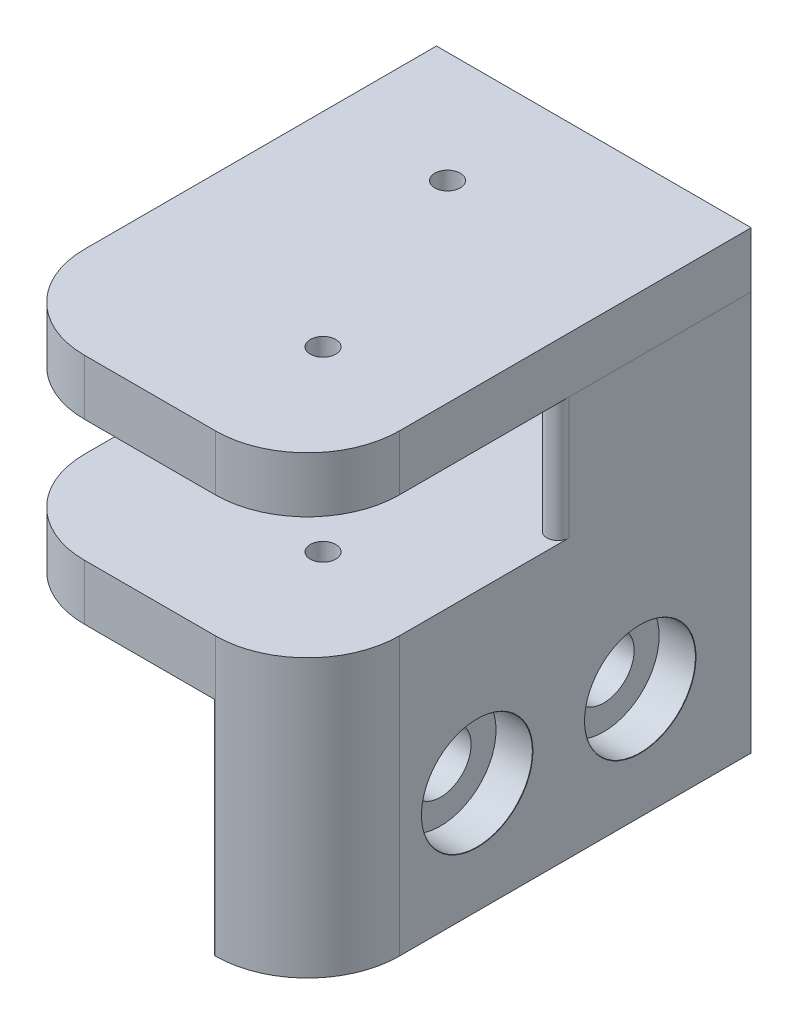
SolidWorks part; units mm, degrees
ref_plane "Front Plane" through (0, 0, 0) normal (0, 0, 1) x (1, 0, 0)
ref_plane "Top Plane" through (0, 0, 0) normal (0, 1, 0) x (1, 0, 0)
ref_plane "Right Plane" through (0, 0, 0) normal (1, 0, 0) x (0, 0, -1)
sketch "Sketch1" plane through (0, 0, 0) normal (0, 1, 0) x (1, 0, 0)
  line L1 (-14.185, -20) -> (14.185, -20)
  line L2 (-14.185, -20) -> (-14.185, 20)
  line L3 (-14.185, 20) -> (14.185, 20)
  line L4 (14.185, -20) -> (14.185, 20)
  line L5 (-14.185, -20) -> (14.185, 20) construction
  line L6 (-14.185, 20) -> (14.185, -20) construction
  point P0 (0, 0)
  dimension "D1" = 28.37
  dimension "D2" = 40
extrude "Boss-Extrude1" add sketch "Sketch1" along normal blind 5
sketch "Sketch2" plane through (0, 0, 0) normal (0, -1, 0) x (1, 0, 0)
  line L0 (-14.185, -20) -> (-14.185, 20) construction
  line L2 (14.185, -20) -> (-14.185, -20) construction
  circle A0 centre (-3.185, -10) radius 1.1485
  dimension "D1" = 11
  dimension "D2" = 10
extrude "Cut-Extrude1" cut sketch "Sketch2" against normal through all
sketch "Sketch4" plane through (0, 0, 0) normal (0, -1, 0) x (1, 0, 0)
  line L1 (5.815, 20) -> (14.185, 20)
  line L2 (5.815, 20) -> (5.815, -20)
  line L3 (5.815, -20) -> (14.185, -20)
  line L4 (14.185, 20) -> (14.185, -20)
  line L5 (14.185, 20) -> (14.185, -20) construction
  line L6 (14.185, -20) -> (-14.185, -20) construction
  dimension "D1" = 8.37
extrude "Boss-Extrude2" add sketch "Sketch4" along normal blind 20
sketch "Sketch5" plane through (0, 5, 0) normal (0, 1, 0) x (1, 0, 0)
  line L0 (14.185, 20) -> (6.815, 20)
  line L1 (14.185, 20) -> (-14.185, 20) construction
  line L2 (6.815, 20) -> (6.815, 12.1812)
  line L3 (6.815, 12.1812) -> (14.185, 0)
  line L4 (14.185, -20) -> (14.185, 20) construction
  line L5 (14.185, 0) -> (14.185, 20)
  circle A0 centre (-3.185, 10) radius 1.1485 construction
  dimension "D1" = 10
extrude "Boss-Extrude3" add sketch "Sketch5" along normal blind 11
sketch "Sketch6" plane through (0, 16, 0) normal (0, 1, 0) x (1, 0, 0)
  line L0 (14.185, 20) -> (-14.185, 20)
  line L1 (-14.185, 20) -> (-14.185, -20)
  line L2 (-14.185, -20) -> (14.185, -20)
  line L3 (14.185, -20) -> (14.185, 20)
extrude "Boss-Extrude4" add sketch "Sketch6" along normal blind 5
sketch "Sketch3" plane through (0, 0, 0) normal (0, -1, 0) x (1, 0, 0)
  line L1 (-14.185, -20) -> (-14.185, 20) construction
  circle A1 centre (4.185, 8.5926) radius 1.15
  circle A3 centre (-3.185, -10) radius 20 construction
  dimension "D1" = 18.37
  dimension "D2" = 2.3
  dimension "D3" = 40
extrude "Cut-Extrude2" cut sketch "Sketch3" against normal through all
sketch "Sketch7" plane through (0, 16, 0) normal (0, -1, 0) x (1, 0, 0)
  line L0 (5.815, -20) -> (-14.185, -20) construction
  line L1 (-14.185, -20) -> (-14.185, 20) construction
  circle A0 centre (-3.185, -10) radius 1.15
  circle A1 centre (-3.185, -10) radius 20 construction
  circle A2 centre (4.185, 8.5926) radius 1.15
  dimension "D1" = 10
  dimension "D2" = 2.3
  dimension "D3" = 11
  dimension "D4" = 2.3
  dimension "D6" = 40
  dimension "D5" = 18.37
extrude "Cut-Extrude3" cut sketch "Sketch7" against normal up to next (5 mm away)
fillet "Fillet1" radius 1 1 edges at (14.185, 10.5, 0)
fillet "Fillet2" radius 8.3 4 edges at (-14.185, 2.5, 20) (-14.185, 18.5, 20) (14.185, 18.5, 20) (14.185, -7.5, 20)
ref_plane "Plane1" through (0, 16, 0) normal (0, -1, 0) x (-1, 0, 0)
split "Split1" trim tools "Plane1" bodies to split 110 resulting bodies 111 112
mirror "Mirror1" [suppressed]
delete or keep bodies "Body-Delete/Keep 1" [suppressed] type delete bodies bodies 111 112
sketch "Sketch8" plane through (14.185, 0, 0) normal (1, 0, 0) x (0, 0, -1)
  line L0 (20, -20) -> (-11.7, -20) construction
  line L1 (20, 16) -> (20, -20) construction
  line L2 (-11.7, 5) -> (-11.7, -20) construction
  point P0 (10, -10)
  point P1 (-4.7, -10)
  dimension "D1" = 10
  dimension "D2" = 10
  dimension "D3" = 10
  dimension "D4" = 7
hole_wizard "CBORE for M5 Cheese Head Screw1" positions "3DSketch1" profile "Sketch10" counterbore size "M5" standard "ISO" end condition up to next
sketch3d "3DSketch1"
  point P0 (14.185, -10, 4.7)
  point P3 (14.185, -10, -10)
sketch "Sketch10" plane through (14.185, -10, 4.7) normal (0, 1, 0) x (0, 0, -1)
  line L0 (0, 0) -> (0, 8.37)
  line L1 (0, 8.37) -> (2.75, 8.37)
  line L3 (2.75, 8.37) -> (2.75, 3.3)
  line L4 (5, 3.3) -> (2.75, 3.3)
  line L5 (5, 3.3) -> (5, 0.025)
  line L6 (5, 0.025) -> (5.025, 0)
  line L7 (5.025, 0) -> (0, 0)
  line L8 (-5, 0.025) -> (-5.025, 0) construction
  line L11 (0, -6.35) -> (0, 107.95) construction
  dimension "Thru Hole Dia." = 5.5
  dimension "Thru Hole Depth" = 8.37
  dimension "C'Bore Dia." = 10
  dimension "C'Bore Depth" = 3.3
  dimension "Near C'Sink Dia." = 10.05
  dimension "Near C'Sink Angle" = 90
sketch "Sketch11" [suppressed] plane through (14.185, 0, 0) normal (-1, 0, 0) x (0, 0, 1)
  line L0 (-20, -20) -> (11.7, -20) construction
  line L1 (11.7, 5) -> (11.7, -20) construction
  line L2 (-20, 16) -> (-20, -20) construction
  point P0 (-10, -10)
  point P1 (4.7, -10)
  dimension "D1" = 10
  dimension "D2" = 10
  dimension "D3" = 7
  dimension "D4" = 10
hole_wizard "CBORE for M5 Cheese Head Screw2" [suppressed] positions "3DSketch2" profile "Sketch12" counterbore size "M5" standard "ISO"
sketch3d "3DSketch2"
  point P0 (14.185, -10, -10)
  point P3 (14.185, -10, 4.7)
sketch "Sketch12" plane through (14.185, -10, -10) normal (0, 1, 0) x (0, 0, 1)
  line L0 (0, 0) -> (0, 8.371)
  line L1 (0, 8.371) -> (2.75, 8.371)
  line L3 (2.75, 8.371) -> (2.75, 3.3)
  line L4 (5, 3.3) -> (2.75, 3.3)
  line L5 (5, 3.3) -> (5, 0.025)
  line L6 (5, 0.025) -> (5.025, 0)
  line L7 (5.025, 0) -> (0, 0)
  line L8 (-5, 0.025) -> (-5.025, 0) construction
  line L11 (0, -6.35) -> (0, 107.95) construction
  dimension "Thru Hole Dia." = 5.5
  dimension "Thru Hole Depth" = 8.371
  dimension "C'Bore Dia." = 10
  dimension "C'Bore Depth" = 3.3
  dimension "Near C'Sink Dia." = 10.05
  dimension "Near C'Sink Angle" = 90
